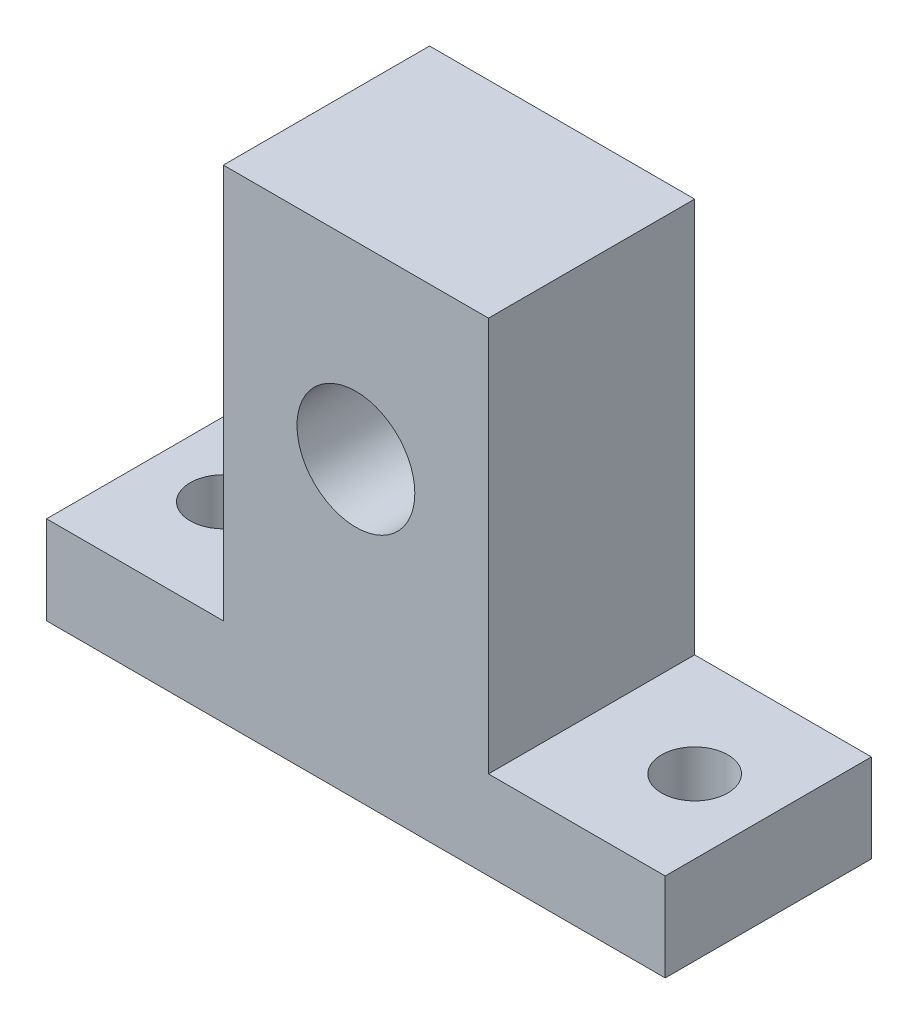
SolidWorks part; units mm, degrees
ref_plane "前视基准面" through (0, 0, 0) normal (0, 0, 1) x (1, 0, 0)
ref_plane "上视基准面" through (0, 0, 0) normal (0, 1, 0) x (1, 0, 0)
ref_plane "右视基准面" through (0, 0, 0) normal (1, 0, 0) x (0, 0, -1)
sketch "草图1" plane through (0, 0, 0) normal (0, 0, 1) x (1, 0, 0)
  line L0 (-9, 12.8) -> (9, 12.8)
  line L1 (9, 12.8) -> (9, -14)
  line L2 (9, -14) -> (21, -14)
  line L3 (21, -14) -> (21, -20)
  line L4 (21, -20) -> (-21, -20)
  line L5 (-21, -20) -> (-21, -14)
  line L6 (-21, -14) -> (-9, -14)
  line L7 (-9, -14) -> (-9, 12.8)
  circle A0 centre (0, 0) radius 4
  dimension "D1" = 8
  dimension "D2" = 42
  dimension "D3" = 18
  dimension "D4" = 9
  dimension "D5" = 21
  dimension "D6" = 20
  dimension "D7" = 32.8
  dimension "D8" = 6
  dimension "D9" = 6
extrude "凸台-拉伸1" add sketch "草图1" along normal blind 14
sketch "草图2" plane through (0, -14, 0) normal (0, 1, 0) x (1, 0, 0)
  line L0 (21, 0) -> (9, 0) construction
  line L1 (-9, 0) -> (-21, 0) construction
  line L2 (-21, -14) -> (-21, 0) construction
  line L3 (21, -14) -> (21, 0) construction
  circle A0 centre (-16, -7) radius 2.25
  circle A1 centre (16, -7) radius 2.25
  dimension "D1" = 4.5
  dimension "D2" = 4.5
  dimension "D3" = 7
  dimension "D4" = 7
  dimension "D5" = 5
  dimension "D6" = 5
extrude "切除-拉伸1" cut sketch "草图2" against normal through all
